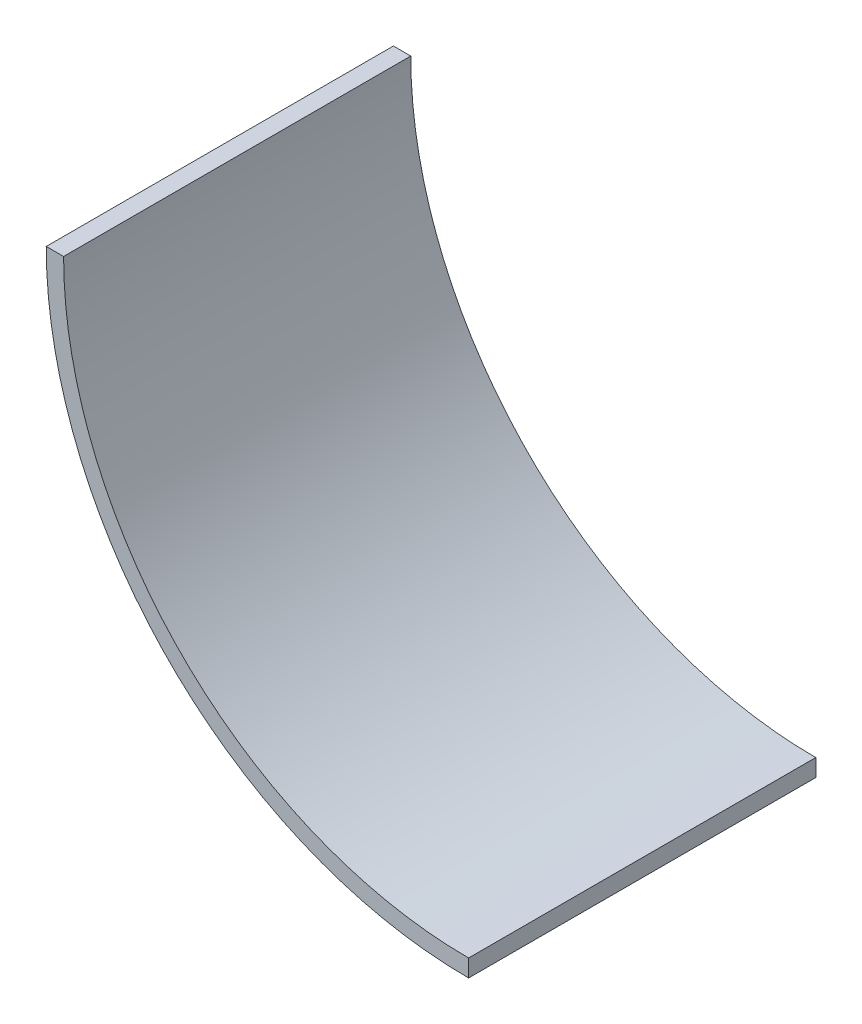
SolidWorks part; units mm, degrees
ref_plane "Plan de face" through (0, 0, 0) normal (0, 0, 1) x (1, 0, 0)
ref_plane "Plan de dessus" through (0, 0, 0) normal (0, 1, 0) x (1, 0, 0)
ref_plane "Plan de droite" through (0, 0, 0) normal (1, 0, 0) x (0, 0, -1)
sketch "Esquisse1" plane through (0, 0, 0) normal (0, 0, 1) x (1, 0, 0)
  arc A0 (-35, 0) -> (0, -35) centre (0, 0) ccw
extrude "Extru.-Mince1" add sketch "Esquisse1" along normal blind 30 thin
